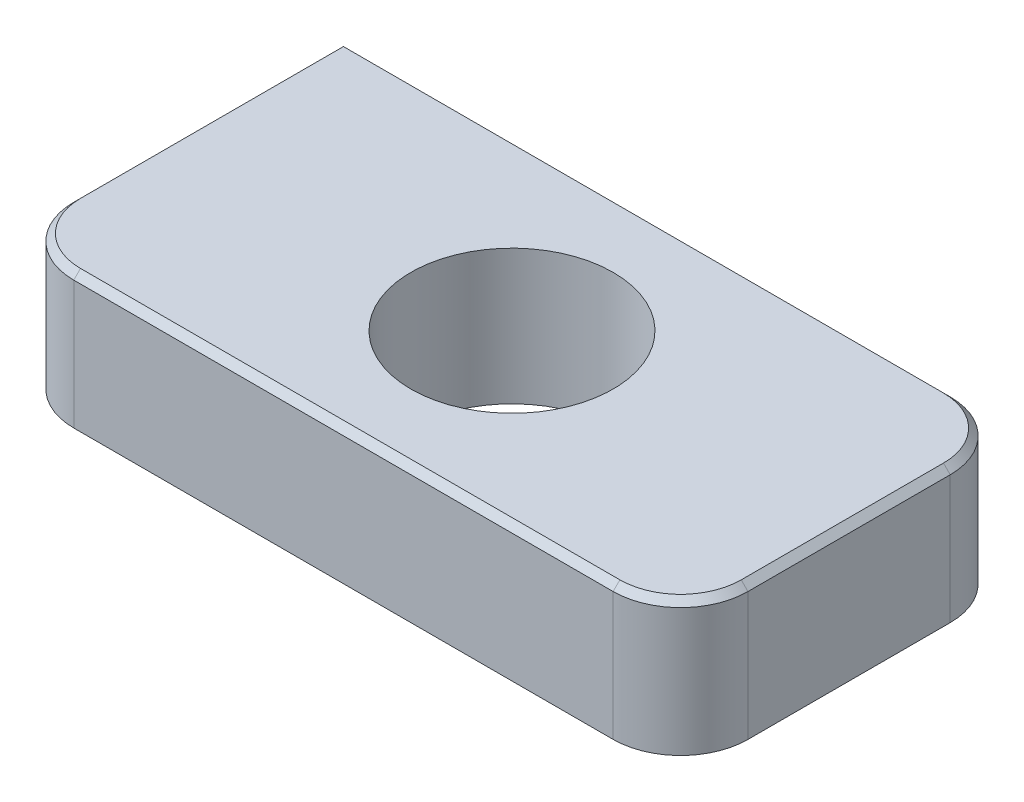
SolidWorks part; units mm, degrees
ref_plane "Front Plane" through (0, 0, 0) normal (0, 0, 1) x (1, 0, 0)
ref_plane "Top Plane" through (0, 0, 0) normal (0, 1, 0) x (1, 0, 0)
ref_plane "Right Plane" through (0, 0, 0) normal (1, 0, 0) x (0, 0, -1)
sketch "Sketch1" plane through (0, 0, 0) normal (0, 1, 0) x (1, 0, 0)
  line L1 (-50, 25) -> (50, 25)
  line L2 (-50, 25) -> (-50, -25)
  line L3 (-50, -25) -> (50, -25)
  line L4 (50, 25) -> (50, -25)
  line L5 (0, -25) -> (0, 25) construction
  line L6 (-50, 0) -> (50, 0) construction
  point P0 (0, 0)
  dimension "D1" = 100
  dimension "D2" = 50
extrude "Boss-Extrude1" add sketch "Sketch1" along normal blind 20
sketch "Sketch2" plane through (0, 20, 0) normal (0, 1, 0) x (1, 0, 0)
  circle A0 centre (0, 0) radius 15
  dimension "D1" = 30
extrude "Cut-Extrude1" cut sketch "Sketch2" against normal blind 20
fillet "Fillet1" radius 10 3 edges at (50, 10, -25) (50, 10, 25) (-50, 10, 25)
chamfer "Chamfer1" distance 1 angle 45 7 edges at (-5, 20, -25) (47.0711, 20, -22.0711) (-50, 20, -5) (50, 20, 0) (-47.0711, 20, 22.0711) (47.0711, 20, 22.0711) (0, 20, 25)
